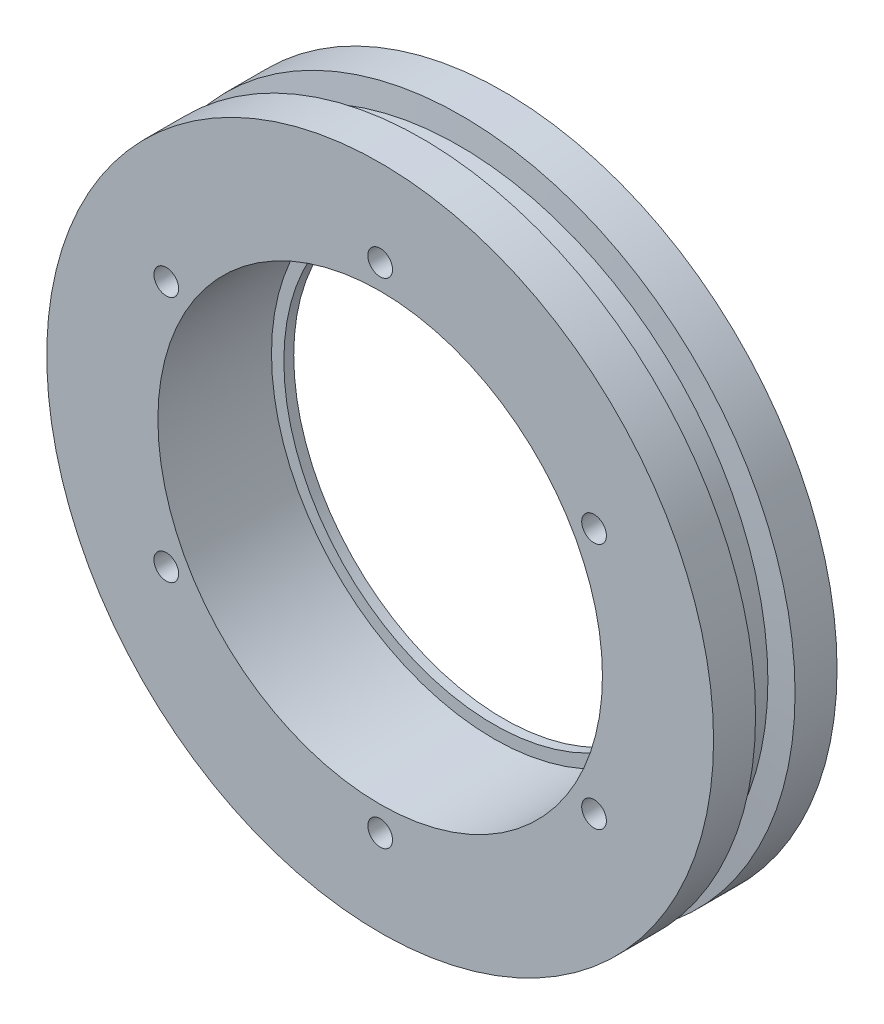
SolidWorks part; units mm, degrees
ref_plane "Front Plane" through (0, 0, 0) normal (0, 0, 1) x (1, 0, 0)
ref_plane "Top Plane" through (0, 0, 0) normal (0, 1, 0) x (1, 0, 0)
ref_plane "Right Plane" through (0, 0, 0) normal (1, 0, 0) x (0, 0, -1)
sketch "Sketch1" plane through (0, 0, 0) normal (0, 1, 0) x (1, 0, 0)
  line L0 (0, 0) -> (0, 42.0226) construction
  line L1 (45, 0) -> (45, 23)
  line L2 (45, 23) -> (42.5, 23)
  line L3 (42.5, 23) -> (42.5, 25)
  line L4 (42.5, 25) -> (67.5, 25)
  line L5 (67.5, 25) -> (67.5, 0)
  line L6 (67.5, 0) -> (45, 0)
  dimension "D1" = 90
  dimension "D2" = 135
  dimension "D3" = 23
  dimension "D4" = 85
  dimension "D5" = 2
revolve "Revolve1" add sketch "Sketch1" angle 360 about L0
hole_wizard "M6 Tapped Hole1" positions "Sketch2" profile "Sketch3" tap size "M6" standard "ISO"
sketch "Sketch2" plane through (0, 0, 0) normal (0, 0, 1) x (1, 0, 0)
  point P0 (0, 50)
  dimension "D1" = 50
sketch "Sketch3" plane through (0, 50, 0) normal (1, 0, 0) x (0, -1, 0)
  line L0 (0, 0) -> (0, 16.5022)
  line L1 (0, 16.5022) -> (2.5, 15)
  line L2 (2.5, 15) -> (2.5, 0)
  line L5 (2.5, 0) -> (0, 0)
  line L10 (0, 16.5022) -> (-2.5, 15) construction
  line L11 (0, -6.35) -> (0, 107.95) construction
  dimension "Tap Drill Dia." = 5
  dimension "Tap Drill Depth" = 15
  dimension "Drill Angle" = 118
cosmetic thread "Hole Thread1" parameters "D1"=12, "D2"=6
pattern_circular "CirPattern1" count 6 over 360 about axis through (0, 0, 0) along (0, 0, 1) of "M6 Tapped Hole1"
sketch "Sketch5" plane through (0, 0, 0) normal (0, 1, 0) x (1, 0, 0)
  line L0 (67.5, 8.5) -> (62.5, 9)
  line L1 (67.5, 0) -> (67.5, 25) construction
  line L2 (62.5, 9) -> (62.5, 16)
  line L3 (62.5, 16) -> (67.5, 16.5)
  line L4 (67.5, 16.5) -> (67.5, 8.5)
  line L5 (62.5, 12.5) -> (67.5, 12.5) construction
  line L6 (62.5, 25) -> (62.5, 0) construction
  line L7 (67.5, 25) -> (-67.5, 25) construction
  line L8 (-67.5, 0) -> (67.5, 0) construction
  line L9 (0, 0) -> (0, 25) construction
  point P14 (62.5, 12.5)
  dimension "D1" = 8
  dimension "D2" = 7
  dimension "D3" = 25
  dimension "D4" = 5
revolve "Cut-Revolve1" cut sketch "Sketch5" angle 360 about L9
move or copy body "Body-Move/Copy1" [suppressed] bodies to move or copy 105
